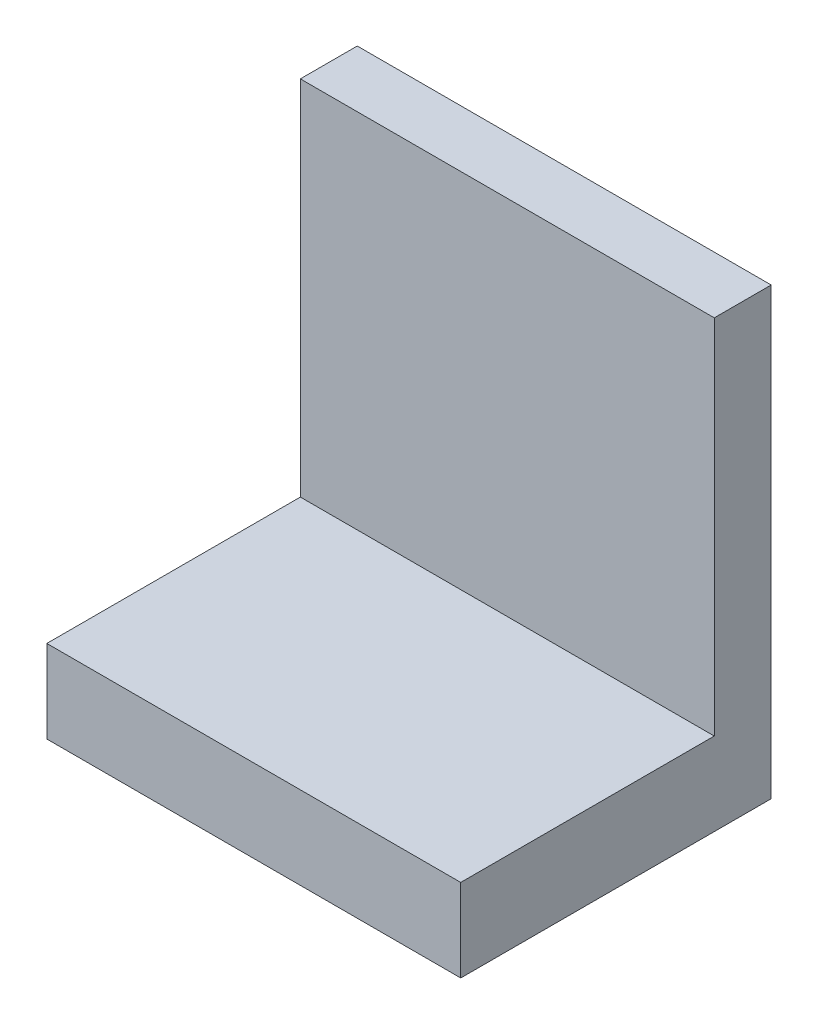
SolidWorks part; units mm, degrees
ref_plane "Front Plane" through (0, 0, 0) normal (0, 0, 1) x (1, 0, 0)
ref_plane "Top Plane" through (0, 0, 0) normal (0, 1, 0) x (1, 0, 0)
ref_plane "Right Plane" through (0, 0, 0) normal (1, 0, 0) x (0, 0, -1)
sketch "Sketch1" plane through (0, 0, 0) normal (0, 1, 0) x (1, 0, 0)
  line L1 (-4, -3) -> (4, -3)
  line L2 (-4, -3) -> (-4, 3)
  line L3 (-4, 3) -> (4, 3)
  line L4 (4, -3) -> (4, 3)
  line L5 (-4, -3) -> (4, 3) construction
  line L6 (-4, 3) -> (4, -3) construction
  point P0 (0, 0)
extrude "Boss-Extrude1" add sketch "Sketch1" along normal blind 1.6
sketch "Sketch2" plane through (0, 1.6, 0) normal (0, 1, 0) x (1, 0, 0)
  line L0 (4, -3) -> (4, 3) construction
  line L1 (-4, 3) -> (4, 3)
  line L2 (-4, 3) -> (-4, 1.9)
  line L3 (-4, 1.9) -> (4, 1.9)
  line L4 (4, 3) -> (4, 1.9)
extrude "Boss-Extrude2" add sketch "Sketch2" along normal blind 7
